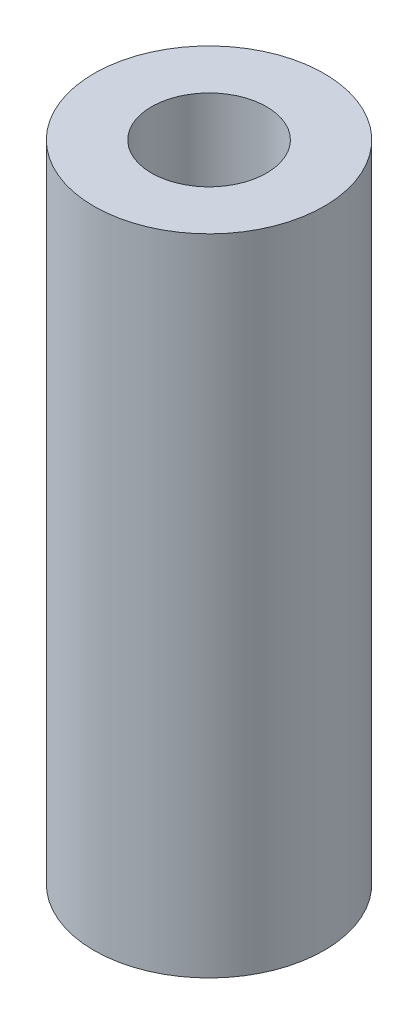
SolidWorks part; units mm, degrees
material "Brass"
ref_plane "Front Plane" through (0, 0, 0) normal (0, 0, 1) x (1, 0, 0)
ref_plane "Top Plane" through (0, 0, 0) normal (0, 1, 0) x (1, 0, 0)
ref_plane "Right Plane" through (0, 0, 0) normal (1, 0, 0) x (0, 0, -1)
sketch "Sketch1" plane through (0, 0, 0) normal (0, 1, 0) x (1, 0, 0)
  circle A0 centre (0, 0) radius 2.5
  circle A1 centre (0, 0) radius 1.25
  dimension "D1" = 2.5
  dimension "D2" = 5
extrude "Boss-Extrude1" add sketch "Sketch1" along normal blind 14
